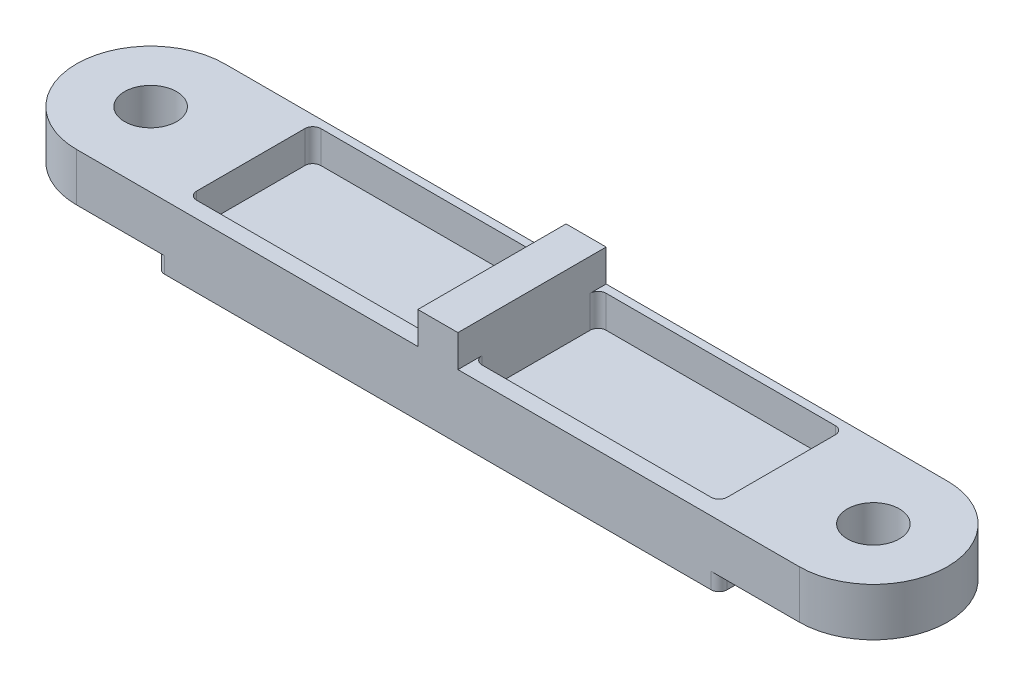
SolidWorks part; units mm, degrees
material "Delrin 2700 NC010, Low Viscosity Acetal Copolymer (SS)"
ref_plane "Front Plane" through (0, 0, 0) normal (0, 0, 1) x (1, 0, 0)
ref_plane "Top Plane" through (0, 0, 0) normal (0, 1, 0) x (1, 0, 0)
ref_plane "Right Plane" through (0, 0, 0) normal (1, 0, 0) x (0, 0, -1)
sketch "Sketch1" plane through (0, 0, 0) normal (0, 1, 0) x (1, 0, 0)
  line L1 (-35.1, -9.25) -> (0, -9.25)
  line L2 (-35.1, -9.25) -> (-35.1, 9.25)
  line L3 (-35.1, 9.25) -> (0, 9.25)
  line L4 (0, -9.25) -> (0, 9.25)
  line L5 (-35.1, -9.25) -> (0, 9.25) construction
  line L6 (-35.1, 9.25) -> (0, -9.25) construction
  point P0 (-17.55, 0)
  point P8 (0, 0)
  dimension "D1" = 35.1
  dimension "D2" = 18.5
extrude "Boss-Extrude1" add sketch "Sketch1" along normal blind 8
sketch "Sketch10" plane through (0, 8, 0) normal (0, 1, 0) x (1, 0, 0)
  line L0 (-35.1, 9.25) -> (-45.1, 9.25)
  line L1 (-35.1, -9.25) -> (-45.1, -9.25)
  line L2 (-35.1, 9.25) -> (-35.1, -9.25)
  arc A0 (-45.1, 9.25) -> (-45.1, -9.25) centre (-45.1, 0) ccw
  circle A1 centre (-45.1, 0) radius 3.25
  dimension "D1" = 6.5
  dimension "D2" = 10
extrude "bolt extrude" add sketch "Sketch10" against normal blind 6
shell "Shell1" [suppressed] thickness 1
sketch "Sketch7" plane through (0, 8, 0) normal (0, 1, 0) x (1, 0, 0)
  line L0 (0, -9.25) -> (0, 9.25) construction
  line L1 (0, -7.25) -> (-33.1, -7.25)
  line L2 (0, -7.25) -> (0, 8.25)
  line L3 (0, 8.25) -> (-33.1, 8.25)
  line L4 (-33.1, -7.25) -> (-33.1, 8.25)
  line L5 (-45.1, -9.25) -> (0, -9.25) construction
  line L6 (0, 9.25) -> (-45.1, 9.25) construction
  line L7 (-35.1, 9.25) -> (-35.1, -9.25) construction
  dimension "D1" = 2
  dimension "D2" = 1
  dimension "D3" = 2
extrude "Cut-Extrude5" cut sketch "Sketch7" against normal offset from surface (4 mm away) 4 up to face at (-17.55, 0, 0)
sketch "Sketch2" plane through (0, 0, 0) normal (0, 1, 0) x (-1, 0, 0)
  line L0 (27, 3.5) -> (9, 3.5) construction
  line L2 (27, 3.5) -> (27, -4.5) construction
  line L3 (27, -4.5) -> (9, -4.5) construction
  line L4 (9, -4.5) -> (9, 3.5) construction
  line L5 (27, -0.5) -> (18.8977, -0.5) construction
  line L6 (17.55, -9.25) -> (17.55, 9.25) construction
  line L7 (0, 7.25) -> (0, -8.25) construction
  line L8 (27, -0.5) -> (0, -0.5) construction
  line L9 (0, -9.25) -> (35.1, -9.25) construction
  line L10 (35.1, 9.25) -> (0, 9.25) construction
  circle A0 centre (27, 3.5) radius 1.75
  circle A1 centre (9, 3.5) radius 1.75
  circle A2 centre (27, -4.5) radius 1.75
  circle A3 centre (9, -4.5) radius 1.75
  circle A5 centre (27, 3.5) radius 2.5 construction
  circle A6 centre (27, -4.5) radius 2.5 construction
  circle A7 centre (9, -4.5) radius 2.5 construction
  circle A8 centre (9, 3.5) radius 2.5 construction
  dimension "D1" = 3.5
  dimension "D4" = 9
  dimension "D5" = 5
  dimension "D2" = 18
  dimension "D3" = 8
extrude "Cut-Extrude1" [suppressed] cut sketch "Sketch2" along normal through all
sketch "Sketch3" [suppressed] plane through (0, 5, 0) normal (0, 1, 0) x (1, 0, 0)
  line L1 (-2.9573, -5.1559) -> (2.9865, -5.139)
  line L2 (2.9865, -5.139) -> (5.9438, 0.0169)
  line L3 (5.9438, 0.0169) -> (2.9573, 5.1559)
  line L4 (2.9573, 5.1559) -> (-2.9865, 5.139)
  line L5 (-2.9865, 5.139) -> (-5.9438, -0.0169)
  line L6 (-5.9438, -0.0169) -> (-2.9573, -5.1559)
  circle A0 centre (0, 0) radius 2.6 construction
  circle A1 centre (0, 0) radius 5.1475 construction
  dimension "D1" = 5.2
extrude "Cut-Extrude2" [suppressed] cut sketch "Sketch3" against normal blind 0.5
sketch "Sketch4" plane through (-35.1, 0, 0) normal (-1, 0, 0) x (0, 0, 1)
  line L0 (-9.25, 8) -> (9.25, 8) construction
  line L1 (-5, 11.5) -> (9.25, 11.5)
  line L3 (-5, 6) -> (9.25, 6)
  line L4 (9.25, 11.5) -> (9.25, 6)
  line L5 (0, 6) -> (0, 0) construction
  line L11 (-9.25, 0) -> (9.25, 0) construction
  line L12 (-5, 6) -> (-5, 11.5)
  dimension "D1" = 5
  dimension "D2" = 5.5
extrude "Cut-Extrude3" [suppressed] cut sketch "Sketch4" against normal offset from surface (5 mm away) 3
mirror "Mirror1" about plane through (0, 0, 0) normal (1, 0, 0) of bodies 111 105
sketch "Sketch5" plane through (0, 0, 0) normal (0, 1, 0) x (1, 0, 0)
  line L0 (33.1, 0.5) -> (0, 0.5) construction
  line L1 (33.1, 8.25) -> (33.1, -7.25) construction
  line L4 (0, 0.5) -> (0, 0) construction
  circle A0 centre (0, 0.5) radius 2.75
  dimension "D1" = 5.5
extrude "Cut-Extrude4" [suppressed] cut sketch "Sketch5" along normal through all
sketch "Sketch6" [suppressed] plane through (0, 4, 0) normal (0, 1, 0) x (1, 0, 0)
  circle A0 centre (0, 0.5) radius 6.25
  circle A1 centre (0, 0.5) radius 5.25
  circle A2 centre (0, 0.5) radius 2.75 construction
  dimension "D1" = 10.5
  dimension "D2" = 1
extrude "Boss-Extrude2" [suppressed] add sketch "Sketch6" along normal blind 3.5
fillet "Fillet3" [suppressed] radius 1
fillet "Fillet4" [suppressed] radius 0.5
fillet "Fillet5" [suppressed] radius 0.5
fillet "Fillet7" [suppressed] radius 1
fillet "Fillet8" [suppressed] radius 1
sketch "Sketch8" plane through (0, 4, 0) normal (0, 1, 0) x (1, 0, 0)
  line L1 (2.5, -9.25) -> (-2.5, -9.25)
  line L2 (2.5, -9.25) -> (2.5, 9.25)
  line L3 (2.5, 9.25) -> (-2.5, 9.25)
  line L4 (-2.5, -9.25) -> (-2.5, 9.25)
  line L8 (45.1, 9.25) -> (-45.1, 9.25) construction
  line L9 (-45.1, -9.25) -> (45.1, -9.25) construction
  point P4 (-2.5, 9.25)
  point P7 (-2.5, -9.25)
  dimension "D1" = 2.5
  dimension "D2" = 2.5
extrude "Boss-Extrude3" add sketch "Sketch8" along normal blind 8
fillet "Fillet6" radius 1 12 edges at (-35.1, 1, 9.25) (-35.1, 1, -9.25) (-33.1, 6, -8.25) (-33.1, 6, 7.25) (35.1, 1, -9.25) (35.1, 1, 9.25) (33.1, 6, -8.25) (33.1, 6, 7.25) (-2.5, 6, 7.25) (2.5, 6, 7.25) (2.5, 6, -8.25) (-2.5, 6, -8.25)
